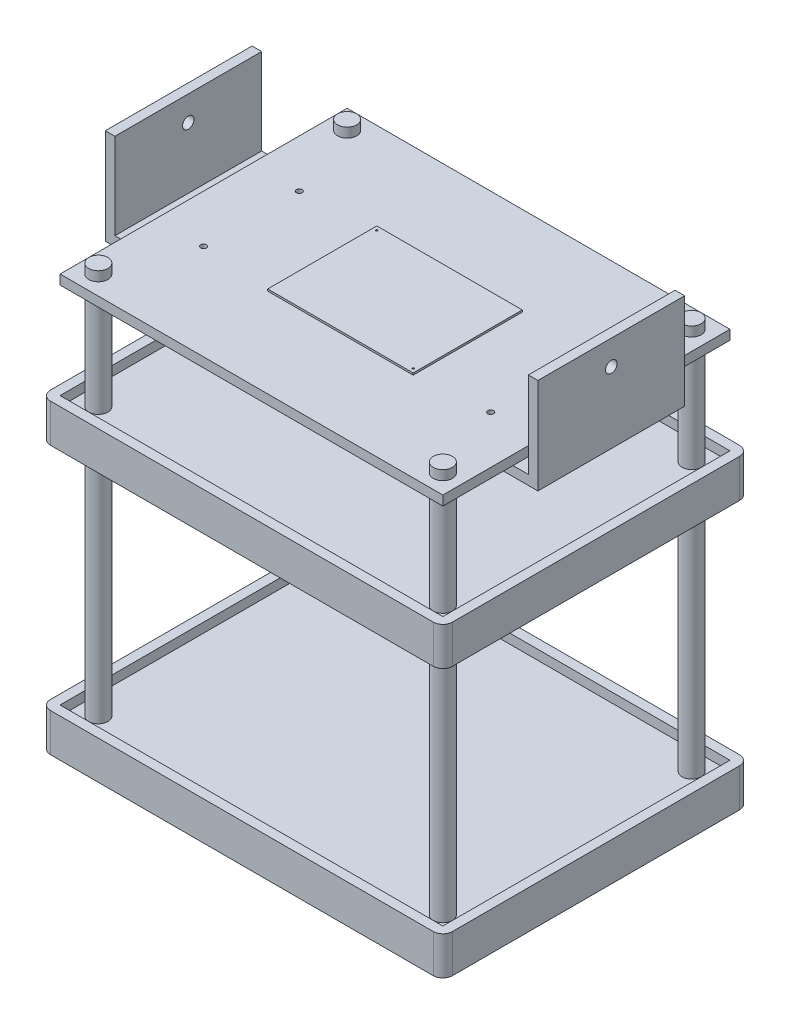
SolidWorks part; units mm, degrees
ref_plane "Front Plane" through (0, 0, 0) normal (0, 0, 1) x (1, 0, 0)
ref_plane "Top Plane" through (0, 0, 0) normal (0, 1, 0) x (1, 0, 0)
ref_plane "Right Plane" through (0, 0, 0) normal (1, 0, 0) x (0, 0, -1)
sketch "Sketch1" plane through (0, 0, 0) normal (0, 1, 0) x (1, 0, 0)
  line L1 (-100, 75) -> (100, 75)
  line L2 (-100, 75) -> (-100, -75)
  line L3 (-100, -75) -> (100, -75)
  line L4 (100, 75) -> (100, -75)
  line L5 (-100, 75) -> (100, -75) construction
  line L6 (-100, -75) -> (100, 75) construction
  point P0 (0, 0)
  dimension "D1" = 200
  dimension "D2" = 150
extrude "Boss-Extrude1" add sketch "Sketch1" along normal blind 5
sketch "Sketch2" plane through (0, 5, 0) normal (0, 1, 0) x (1, 0, 0)
  line L0 (-100, 75) -> (-100, -75) construction
  line L1 (100, 75) -> (-100, 75) construction
  line L2 (0, 73.0671) -> (0, 83.6614) construction
  line L3 (0, 83.6614) -> (0, -94.4748) construction
  line L4 (-110.8687, 0) -> (113.9791, 0) construction
  circle A0 centre (-90, 65) radius 5
  circle A1 centre (90, 65) radius 5
  circle A2 centre (90, -65) radius 5
  circle A3 centre (-90, -65) radius 5
  dimension "D1" = 10
  dimension "D2" = 10
  dimension "D3" = 10
extrude "Cut-Extrude1" cut sketch "Sketch2" against normal blind 10
ref_plane "Plane1" through (0, 140, 0) normal (0, 1, 0) x (1, 0, 0)
sketch "Sketch3" plane through (0, 140, 0) normal (0, 1, 0) x (1, 0, 0)
  line L1 (-100, 75) -> (100, 75)
  line L2 (-100, 75) -> (-100, -75)
  line L3 (-100, -75) -> (100, -75)
  line L4 (100, 75) -> (100, -75)
  line L5 (-100, 75) -> (100, -75) construction
  line L6 (-100, -75) -> (100, 75) construction
  circle A0 centre (-90, 65) radius 5
  circle A1 centre (90, 65) radius 5
  circle A2 centre (-90, -65) radius 5
  circle A3 centre (90, -65) radius 5
  point P0 (0, 0)
extrude "Boss-Extrude2" add sketch "Sketch3" along normal blind 5 separate body
ref_plane "Plane4" through (0, 200, 0) normal (0, 1, 0) x (1, 0, 0)
sketch "Sketch4" plane through (0, 200, 0) normal (0, 1, 0) x (1, 0, 0)
  line L1 (-100, 75) -> (100, 75)
  line L2 (-100, 75) -> (-100, -75)
  line L3 (-100, -75) -> (100, -75)
  line L4 (100, 75) -> (100, -75)
  line L5 (-100, 75) -> (100, -75) construction
  line L6 (-100, -75) -> (100, 75) construction
  circle A0 centre (-90, 65) radius 5
  circle A1 centre (90, 65) radius 5
  circle A2 centre (90, -65) radius 5
  circle A3 centre (-90, -65) radius 5
  point P1 (0, 0)
extrude "Boss-Extrude3" add sketch "Sketch4" along normal blind 5 separate body
sketch "Sketch5" plane through (0, 205, 0) normal (0, 1, 0) x (1, 0, 0)
  circle A0 centre (-90, -65) radius 5
sketch "Sketch17" plane through (0, 200, 0) normal (0, -1, 0) x (1, 0, 0)
  circle A0 centre (-90, -65) radius 5.3637
sketch "Sketch21" plane through (0, 5, 0) normal (0, 1, 0) x (1, 0, 0)
  circle A0 centre (-90, -65) radius 5
  circle A1 centre (-90, 65) radius 5
  circle A2 centre (90, 65) radius 5
  circle A3 centre (90, -65) radius 5
  dimension "D1" = 10
  dimension "D2" = 10
  dimension "D3" = 10
  dimension "D4" = 10
extrude "Boss-Extrude13" add sketch "Sketch21" along normal blind 205
sketch "Sketch22" plane through (0, 5, 0) normal (0, 1, 0) x (1, 0, 0)
  circle A0 centre (-90, 65) radius 5
  circle A1 centre (-90, -65) radius 5
  circle A2 centre (90, -65) radius 5
  circle A3 centre (90, 65) radius 5
  dimension "D1" = 10
  dimension "D2" = 10
  dimension "D3" = 10
  dimension "D4" = 10
extrude "Boss-Extrude14" add sketch "Sketch22" against normal blind 15
sketch "Sketch23" plane through (0, 205, 0) normal (0, 1, 0) x (1, 0, 0)
  line L0 (-100, 75) -> (-100, -75) construction
  line L1 (-140.155, 0) -> (119.4256, 0) construction
  line L2 (0, -2.75) -> (0, 2.75) construction
  circle A0 centre (-75, 25) radius 1.5
  circle A1 centre (-75, -25) radius 1.5
  circle A2 centre (75, -25) radius 1.5
  circle A3 centre (75, 25) radius 1.5
  dimension "D1" = 3
  dimension "D2" = 25
  dimension "D3" = 25
extrude "Cut-Extrude2" cut sketch "Sketch23" against normal blind 10
sketch "Sketch27" plane through (0, 205, 0) normal (0, 1, 0) x (1, 0, 0)
  line L0 (-38, 28.5) -> (38, -28.5) construction
  line L5 (-38, -28.5) -> (38, 28.5) construction
  line L7 (-38, 28.5) -> (38, 28.5)
  line L8 (-38, 28.5) -> (-38, -28.5)
  line L9 (-38, -28.5) -> (38, -28.5)
  line L10 (38, 28.5) -> (38, -28.5)
  circle A0 centre (-36, 26.5) radius 0.5
  circle A1 centre (36, -26.5) radius 0.5
  point P0 (-6.164, -10.787)
  point P5 (0, 0)
  point P11 (0, 0)
  dimension "D3" = 1
  dimension "D6" = 1
  dimension "D1" = 57
  dimension "D2" = 76
  dimension "D4" = 2
  dimension "D5" = 2
  dimension "D7" = 2
  dimension "D8" = 2
extrude "Boss-Extrude16" add sketch "Sketch27" along normal blind 1 contours L8 L7 L10 L9
sketch "Sketch30" plane through (0, 206, 0) normal (0, 1, 0) x (1, 0, 0)
  line L0 (-38, 28.5) -> (-38, -28.5) construction
  line L1 (-38, 28.5) -> (38, 28.5) construction
  line L2 (38, 28.5) -> (38, -28.5) construction
  line L3 (-38, -28.5) -> (38, -28.5) construction
  circle A0 centre (-36, 26.5) radius 0.5
  circle A1 centre (36, -26.5) radius 0.5
  dimension "D1" = 1
  dimension "D4" = 1
  dimension "D2" = 2
  dimension "D3" = 2
  dimension "D5" = 2
  dimension "D6" = 2
extrude "Cut-Extrude3" cut sketch "Sketch30" against normal blind 30
sketch "Sketch35" plane through (0, 0, 0) normal (0, -1, 0) x (-1, 0, 0)
  line L1 (100, -75) -> (-100, -75)
  line L2 (100, -75) -> (100, 75)
  line L3 (100, 75) -> (-100, 75)
  line L4 (-100, -75) -> (-100, 75)
  line L5 (100, -75) -> (-100, 75) construction
  line L6 (100, 75) -> (-100, -75) construction
  line L7 (105, -80) -> (-105, -80)
  line L8 (105, -80) -> (105, 80)
  line L9 (105, 80) -> (-105, 80)
  line L10 (-105, -80) -> (-105, 80)
  line L11 (105, -80) -> (-105, 80) construction
  line L12 (105, 80) -> (-105, -80) construction
  point P0 (0, 0)
  point P6 (0, 0)
  dimension "D1" = 150
  dimension "D2" = 160
  dimension "D3" = 200
  dimension "D4" = 210
extrude "Boss-Extrude19" add sketch "Sketch35" along normal mid plane 20 separate body
fillet "Fillet4" radius 5 4 edges at (105, 0, 80) (105, 0, -80) (-105, 0, 80) (-105, 0, -80)
sketch "Sketch39" plane through (0, 140, 0) normal (0, -1, 0) x (1, 0, 0)
  line L1 (-100, 75) -> (100, 75)
  line L2 (-100, 75) -> (-100, -75)
  line L3 (-100, -75) -> (100, -75)
  line L4 (100, 75) -> (100, -75)
  line L5 (-100, 75) -> (100, -75) construction
  line L6 (-100, -75) -> (100, 75) construction
  line L7 (-105, 80) -> (105, 80)
  line L8 (-105, 80) -> (-105, -80)
  line L9 (-105, -80) -> (105, -80)
  line L10 (105, 80) -> (105, -80)
  line L11 (-105, 80) -> (105, -80) construction
  line L12 (-105, -80) -> (105, 80) construction
  point P0 (0, 0)
  point P6 (0, 0)
  dimension "D1" = 150
  dimension "D2" = 200
  dimension "D3" = 160
  dimension "D4" = 210
extrude "Boss-Extrude20" add sketch "Sketch39" along normal mid plane 20 separate body
fillet "Fillet5" radius 5 4 edges at (105, 140, 80) (105, 140, -80) (-105, 140, -80) (-105, 140, 80)
sketch "Sketch42" plane through (0, 200, 0) normal (0, -1, 0) x (1, 0, 0)
  line L1 (-7.5, 10) -> (7.5, 10)
  line L2 (-7.5, 10) -> (-7.5, -10)
  line L3 (-7.5, -10) -> (7.5, -10)
  line L4 (7.5, 10) -> (7.5, -10)
  line L5 (-7.5, 10) -> (7.5, -10) construction
  line L6 (-7.5, -10) -> (7.5, 10) construction
  line L7 (-70.7403, -17.1967) -> (-45.7403, -17.1967)
  line L8 (-70.7403, -17.1967) -> (-70.7403, 32.8033)
  line L9 (-70.7403, 32.8033) -> (-45.7403, 32.8033)
  line L10 (-45.7403, -17.1967) -> (-45.7403, 32.8033)
  line L11 (-70.7403, -17.1967) -> (-45.7403, 32.8033) construction
  line L12 (-70.7403, 32.8033) -> (-45.7403, -17.1967) construction
  line L13 (15.7, 23.8618) -> (59, 23.8618)
  line L14 (15.7, 23.8618) -> (15.7, -19.4382)
  line L15 (15.7, -19.4382) -> (59, -19.4382)
  line L16 (59, 23.8618) -> (59, -19.4382)
  line L17 (15.7, 23.8618) -> (59, -19.4382) construction
  line L18 (15.7, -19.4382) -> (59, 23.8618) construction
  point P0 (0, 0)
  point P6 (-58.2403, 7.8033)
  point P11 (37.35, 2.2118)
  dimension "D1" = 20
  dimension "D2" = 15
  dimension "D3" = 50
  dimension "D4" = 25
  dimension "D5" = 43.3
  dimension "D6" = 43.3
  dimension "D7" = 8.2
extrude "Boss-Extrude23" add sketch "Sketch42" along normal blind 1
sketch "Sketch46" plane through (0, 200, 0) normal (0, -1, 0) x (-1, 0, 0)
  line L0 (-196.0871, 0) -> (303.0775, 0) construction
  line L5 (100, -75) -> (100, 75) construction
  line L6 (0, 82.5) -> (0, -82.5) construction
  line L7 (-108, 38.3353) -> (-108, -38.3353)
  line L8 (78, 38.3353) -> (108, 38.3353)
  line L9 (78, 38.3353) -> (78, -38.3353)
  line L10 (78, -38.3353) -> (108, -38.3353)
  line L11 (108, 38.3353) -> (108, -38.3353)
  line L12 (78, 38.3353) -> (108, -38.3353) construction
  line L13 (78, -38.3353) -> (108, 38.3353) construction
  line L14 (-78, -38.3353) -> (-108, -38.3353)
  line L15 (-78, 38.3353) -> (-78, -38.3353)
  line L16 (-78, 38.3353) -> (-108, 38.3353)
  point P0 (122.8294, -19.1676)
  point P6 (93, 0)
  dimension "D1" = 22
  dimension "D2" = 30
extrude "Boss-Extrude24" add sketch "Sketch46" along normal blind 5
sketch "Sketch48" plane through (-108, 0, 0) normal (-1, 0, 0) x (0, 0, 1)
  line L1 (-38.3353, 195) -> (38.3353, 195)
  line L2 (-38.3353, 195) -> (-38.3353, 245)
  line L3 (-38.3353, 245) -> (38.3353, 245)
  line L4 (38.3353, 195) -> (38.3353, 245)
  dimension "D1" = 50
extrude "Boss-Extrude25" add sketch "Sketch48" along normal blind 5
sketch "Sketch49" plane through (-113, 0, 0) normal (-1, 0, 0) x (0, 0, 1)
  line L1 (-38.3353, 195) -> (38.3353, 195) construction
  circle A0 centre (0, 232) radius 3
  dimension "D2" = 6
  dimension "D1" = 37
extrude "Cut-Extrude4" cut sketch "Sketch49" against normal blind 5
sketch "Sketch54" plane through (108, 0, 0) normal (1, 0, 0) x (0, 0, -1)
  line L1 (-38.3353, 195) -> (38.3353, 195)
  line L2 (-38.3353, 195) -> (-38.3353, 245)
  line L3 (-38.3353, 245) -> (38.3353, 245)
  line L4 (38.3353, 195) -> (38.3353, 245)
extrude "Boss-Extrude26" add sketch "Sketch54" along normal blind 5
sketch "Sketch55" plane through (113, 0, 0) normal (1, 0, 0) x (0, 0, -1)
  line L0 (-38.3353, 195) -> (38.3353, 195) construction
  circle A0 centre (0, 232) radius 3
  dimension "D1" = 6
  dimension "D2" = 37
extrude "Cut-Extrude5" cut sketch "Sketch55" against normal blind 5
ref_plane "Plane5" through (0, 65, 0) normal (0, 1, 0) x (1, 0, 0)
